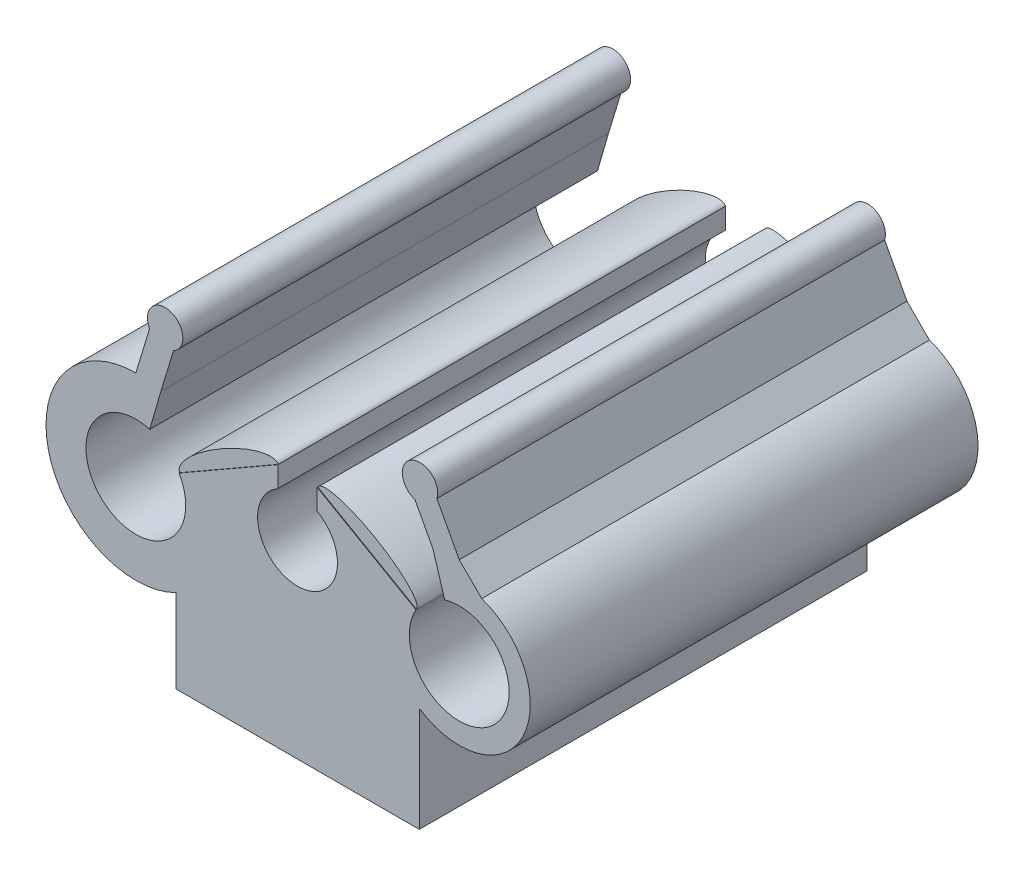
SolidWorks part; units mm, degrees
ref_plane "Ön Düzlem" through (0, 0, 0) normal (0, 0, 1) x (1, 0, 0)
ref_plane "Üst Düzlem" through (0, 0, 0) normal (0, 1, 0) x (1, 0, 0)
ref_plane "Sağ Düzlem" through (0, 0, 0) normal (1, 0, 0) x (0, 0, -1)
sketch "Çizim1" plane through (0, 0, 0) normal (0, 0, 1) x (1, 0, 0)
  line L0 (0, 0) -> (12.2, 0)
  line L1 (12.2, 0) -> (12.2, 4.1689)
  line L3 (0, 4.1689) -> (0, 0)
  line L4 (-2, 12.7) -> (-1.3113, 14.9713)
  line L5 (5.1136, 12.2788) -> (5.1136, 10.9455)
  line L6 (-0.1151, 14.6086) -> (-0.7477, 12.5222)
  line L7 (14.2, 12.7) -> (13.0809, 14.793)
  line L8 (7.0864, 12.2788) -> (7.0864, 10.9455)
  line L9 (11.9786, 14.2036) -> (12.8872, 12.5043)
  line L10 (1.9038, 10.4384) -> (5.1136, 12.2788)
  line L11 (10.2962, 10.4384) -> (7.0864, 12.2788)
  line L12 (10.2962, 10.4384) -> (12.0312, 9.4435)
  line L13 (12.8872, 12.5043) -> (13.4707, 10.5913)
  line L14 (1.9038, 10.4384) -> (0.1688, 9.4435)
  line L15 (-0.7477, 12.5222) -> (-1.3043, 10.6012)
  arc A2 (12.2, 4.1689) -> (14.2, 12.7) centre (14.2, 8.2) ccw
  arc A3 (-2, 12.7) -> (0, 4.1689) centre (-2, 8.2) ccw
  arc A4 (-1.3043, 10.6012) -> (0.1688, 9.4435) centre (-2, 8.2) ccw
  arc A5 (12.0312, 9.4435) -> (13.4707, 10.5913) centre (14.2, 8.2) ccw
  arc A7 (-0.1151, 14.6086) -> (-1.3113, 14.9713) centre (-0.5314, 15.3896) ccw
  arc A8 (13.0809, 14.793) -> (11.9786, 14.2036) centre (12.2343, 15.0509) ccw
  arc A10 (5.1136, 10.9455) -> (7.0864, 10.9455) centre (6.1, 9.5) ccw
  arc A11 (5.1136, 12.2788) -> (4.2001, 11.755) centre (6.1, 9.5) ccw
  arc A12 (7.9999, 11.755) -> (7.0864, 12.2788) centre (6.1, 9.5) ccw
  arc A13 (12.8872, 12.5043) -> (10.2962, 10.4384) centre (14.2, 8.2) ccw
  circle A14 centre (6.1, 9.5) radius 2
  dimension "D3" = 9
  dimension "D4" = 9
  dimension "D9" = 5
  dimension "D10" = 5
  dimension "D13" = 1.77
  dimension "D16" = 1.77
  dimension "D20" = 3.5
  dimension "D11" = 4
  dimension "D1" = 12.2
  dimension "D5" = 2
  dimension "D6" = 2
  dimension "D7" = 8.2
  dimension "D8" = 8.2
  dimension "D17" = 3.7
  dimension "D18" = 3.7
  dimension "D19" = 9.5
extrude "Yükseklik-Ekstrüzyon1" add sketch "Çizim1" along normal blind 22.43 contours A10 L5 L10 L14 A4 L15 L6 A7 L4 A3 L3 L0 L1 A2 L7 A8 L9 L13 A5 L12 L11 L8
sketch "Çizim2" plane through (0, 0, 0) normal (0, 0, -1) x (-1, 0, 0)
  line L0 (-7.0864, 12.2788) -> (-12.0312, 9.4435) construction
  line L1 (-12.0312, 9.4435) -> (-7.0864, 12.2788)
  line L2 (-0.1688, 9.4435) -> (-5.1136, 12.2788) construction
  line L3 (-5.1136, 12.2788) -> (-0.1688, 9.4435)
  ellipse E0 centre (-9.5588, 10.8612) end of major axis (-12.0312, 9.4435) minor radius 0.772 (-7.0864, 12.2788) -> (-12.0312, 9.4435) ccw
  ellipse E1 centre (-2.6412, 10.8612) end of major axis (-0.1688, 9.4435) minor radius 0.77 (-0.1688, 9.4435) -> (-5.1136, 12.2788) ccw
  dimension "D1" = 0.772
extrude "Yükseklik-Ekstrüzyon3" add sketch "Çizim2" against normal blind 22.4
sketch "Çizim3" plane through (0, 0, 0) normal (0, 0, -1) x (-1, 0, 0)
  line L0 (-12.2, 5.2577) -> (-12.2, 4.1689)
  line L2 (-14.2, 12.7) -> (-15.3248, 11.5752)
  arc A0 (-15.3248, 11.5752) -> (-12.2, 5.2577) centre (-14.2, 8.2) ccw
  arc A1 (-14.2, 12.7) -> (-12.2, 4.1689) centre (-14.2, 8.2) ccw
extrude "Kes-Ekstrüzyon3" cut sketch "Çizim3" against normal blind 22.5
